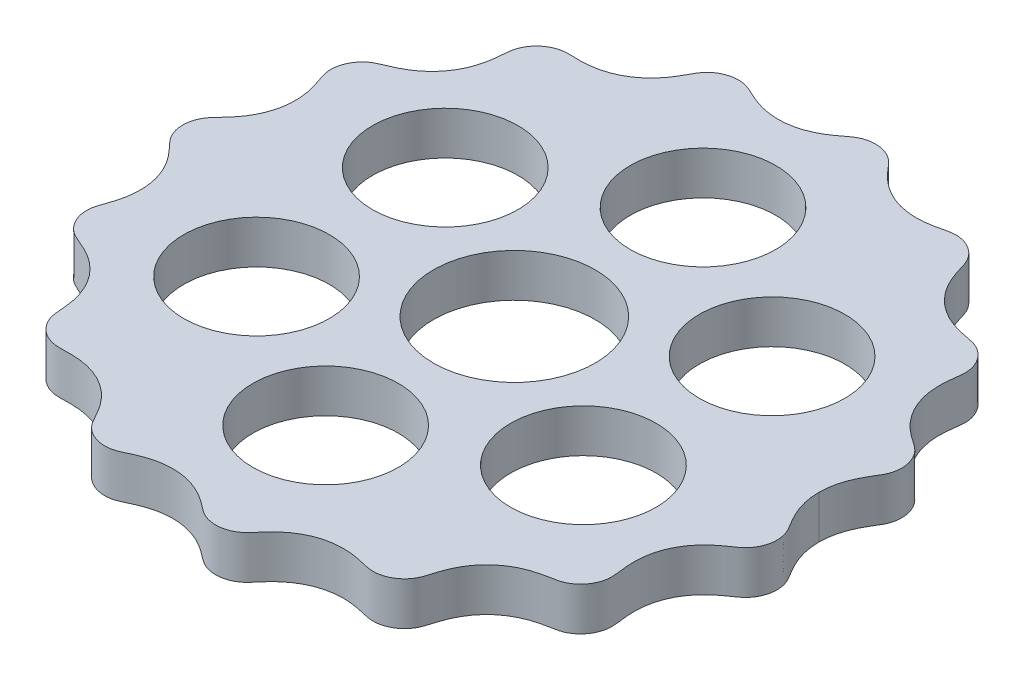
SolidWorks part; units mm, degrees
ref_plane "Front Plane" through (0, 0, 0) normal (0, 0, 1) x (1, 0, 0)
ref_plane "Top Plane" through (0, 0, 0) normal (0, 1, 0) x (1, 0, 0)
ref_plane "Right Plane" through (0, 0, 0) normal (1, 0, 0) x (0, 0, -1)
sketch "Sketch2" plane through (0, 0, 0) normal (0, 1, 0) x (1, 0, 0)
  circle A0 centre (0, 0) radius 35
  circle A1 centre (0, 35) radius 5.5
  circle A2 centre (13.3939, 32.3358) radius 5.5
  circle A3 centre (24.7487, 24.7487) radius 5.5
  circle A4 centre (32.3358, 13.3939) radius 5.5
  circle A5 centre (35, 0) radius 5.5
  circle A6 centre (32.3358, -13.3939) radius 5.5
  circle A7 centre (24.7487, -24.7487) radius 5.5
  circle A8 centre (13.3939, -32.3358) radius 5.5
  circle A9 centre (0, -35) radius 5.5
  circle A10 centre (-13.3939, -32.3358) radius 5.5
  circle A11 centre (-24.7487, -24.7487) radius 5.5
  circle A12 centre (-32.3358, -13.3939) radius 5.5
  circle A13 centre (-35, 0) radius 5.5
  circle A14 centre (-32.3358, 13.3939) radius 5.5
  circle A15 centre (-24.7487, 24.7487) radius 5.5
  circle A16 centre (-13.3939, 32.3358) radius 5.5
  point P14 (0, 0)
  dimension "D1" = 70
  dimension "D2" = 11
  dimension "D3" = 16
sketch "Sketch3" plane through (0, 0, 0) normal (0, 1, 0) x (1, 0, 0)
  line L0 (0, 0) -> (1.25, 0)
  circle A0 centre (1.25, 0) radius 17.5
  circle A1 centre (1.25, 0) radius 7.5
  circle A2 centre (1.25, 17.5) radius 6.75
  circle A3 centre (16.4054, 8.75) radius 6.75
  circle A4 centre (16.4054, -8.75) radius 6.75
  circle A5 centre (1.25, -17.5) radius 6.75
  circle A6 centre (-13.9054, -8.75) radius 6.75
  circle A7 centre (-13.9054, 8.75) radius 6.75
  spline S0 degree 4 poles (31.1366, 6.9847) (31.203, 6.8351) (31.3134, 6.5262) (31.4099, 6.0483) (31.4002, 5.404) (31.2697, 4.8647) (31.0757, 4.4461) (30.8859, 4.1207) (30.7324, 3.8696) (30.5414, 3.5556) (30.3222, 3.1725) (30.1219, 2.7738) (29.947, 2.3583) (29.8196, 1.9985) (29.7291, 1.6992) (29.6529, 1.3958) (29.5916, 1.0892) (29.551, 0.8187) (29.5259, 0.5847) (29.5113, 0.3932) (29.5036, 0.2322) (29.4998, 0.0635) (29.4996, -0.048) (29.5028, -0.2) (29.5088, -0.3457) (29.52, -0.516) (29.5395, -0.7199) (29.5727, -0.9729) (29.6257, -1.2689) (29.6959, -1.5759) (29.7851, -1.8912) (29.9157, -2.2793) (30.102, -2.7349) (30.335, -3.2008) (30.6126, -3.6776) (30.9341, -4.194) (31.2372, -4.7273) (31.4061, -5.3785) (31.4057, -6.1172) (31.2483, -6.8003) (30.9464, -7.4095) (30.5187, -7.9124) (30.0245, -8.2774) (29.5502, -8.595) (29.0554, -8.9568) (28.5566, -9.3788) (28.0713, -9.8763) (27.6188, -10.4563) (27.2335, -11.0884) (26.9232, -11.7651) (26.6937, -12.4782) (26.5492, -13.2173) (26.4929, -13.9285) (26.5065, -14.6008) (26.5673, -15.2309) (26.6512, -15.8162) (26.7167, -16.4473) (26.6264, -17.121) (26.3588, -17.7823) (25.9182, -18.3869) (25.3813, -18.8362) (24.7951, -19.1235) (24.2042, -19.2597) (23.6514, -19.3544) (23.1491, -19.4609) (22.7015, -19.5807) (22.2213, -19.7396) (21.7138, -19.9467) (21.1456, -20.242) (20.5337, -20.6545) (19.9693, -21.14) (19.4622, -21.6938) (19.0208, -22.3087) (18.6716, -22.937) (18.4029, -23.561) (18.1966, -24.1685) (18.0312, -24.7466) (17.8368, -25.3596) (17.4818, -25.9474) (16.963, -26.4532) (16.3026, -26.8344) (15.6052, -27.0309) (14.9186, -27.0444) (14.2906, -26.9063) (13.7073, -26.7605) (13.0779, -26.6354) (12.4032, -26.5561) (11.6845, -26.5443) (10.9313, -26.6191) (10.1981, -26.7814) (9.4956, -27.0274) (8.9144, -27.311) (8.4468, -27.5971) (8.0759, -27.8635) (7.7913, -28.0922) (7.4816, -28.3679) (7.1541, -28.6957) (6.8107, -29.0774) (6.4523, -29.5087) (6.0389, -29.9524) (5.497, -30.3164) (4.8394, -30.5567) (4.0956, -30.636) (3.389, -30.5371) (2.7605, -30.2784) (2.2467, -29.9061) (1.7817, -29.5409) (1.2664, -29.1732) (0.691, -28.8252) (0.0469, -28.5184) (-0.6654, -28.274) (-1.3977, -28.1162) (-2.139, -28.0466) (-2.879, -28.0642) (-3.6075, -28.1661) (-4.2811, -28.3376) (-4.8959, -28.5586) (-5.4566, -28.8062) (-5.9687, -29.0581) (-6.5321, -29.3036) (-7.1813, -29.4226) (-7.8826, -29.3781) (-8.5943, -29.1523) (-9.1983, -28.7803) (-9.6679, -28.2978) (-9.9878, -27.7564) (-10.2605, -27.2379) (-10.5768, -26.6962) (-10.9537, -26.1469) (-11.4088, -25.606) (-11.9502, -25.0925) (-12.5482, -24.6454) (-13.1945, -24.2723) (-13.8806, -23.9779) (-14.596, -23.7658) (-15.292, -23.6421) (-15.9562, -23.5904) (-16.5834, -23.5873) (-17.1688, -23.6104) (-17.7977, -23.6041) (-18.4504, -23.4386) (-19.0745, -23.1016) (-19.6258, -22.5981) (-20.0151, -22.013) (-20.2366, -21.3913) (-20.3057, -20.7807) (-20.3436, -20.2113) (-20.4095, -19.6018) (-20.5256, -18.9589) (-20.7138, -18.2898) (-20.9898, -17.608) (-21.3446, -16.9582) (-21.7755, -16.3511) (-22.2783, -15.7958) (-22.8461, -15.3011) (-23.4339, -14.8967) (-24.0229, -14.5724) (-24.599, -14.31) (-25.1478, -14.0899) (-25.7271, -13.8311) (-26.2654, -13.4161) (-26.7043, -12.8537) (-27.0076, -12.1698) (-27.1282, -11.4802) (-27.084, -10.8288) (-26.9064, -10.2491) (-26.7122, -9.7229) (-26.5247, -9.1481) (-26.3661, -8.5215) (-26.2605, -7.84) (-26.2278, -7.1092) (-26.2792, -6.3728) (-26.4175, -5.6414) (-26.6435, -4.9254) (-26.9163, -4.3218) (-27.1985, -3.8299) (-27.4942, -3.3917) (-27.7933, -3.0033) (-28.1536, -2.592) (-28.5722, -2.1595) (-28.9092, -1.79) (-29.1246, -1.4556) (-29.2527, -1.1931) (-29.3238, -1.0179) (-29.3829, -0.8388) (-29.4302, -0.6555) (-29.4612, -0.4933) (-29.4803, -0.3554) (-29.4914, -0.2338) (-29.4973, -0.1324) (-29.5007, -0.0226) (-29.5, 0.059) (-29.4956, 0.1702) (-29.4865, 0.2945) (-29.4732, 0.4119) (-29.4519, 0.545) (-29.4193, 0.6991) (-29.3684, 0.8884) (-29.2999, 1.0847) (-29.211, 1.2861) (-29.099, 1.4891) (-28.9873, 1.6605) (-28.8641, 1.8237) (-28.732, 1.9798) (-28.56, 2.1688) (-28.311, 2.4302) (-27.9922, 2.7711) (-27.6241, 3.2099) (-27.2613, 3.7219) (-26.8678, 4.4005) (-26.5022, 5.2703) (-26.3208, 6.0377) (-26.2588, 6.6626) (-26.2483, 6.9757) knots 0 0 0 0 0 0.005587 0.011173 0.016507 0.02184 0.02435 0.026861 0.029371 0.031882 0.036903 0.041924 0.044592 0.04726 0.049928 0.052596 0.055264 0.057932 0.059266 0.0606 0.061934 0.063268 0.064442 0.065615 0.066789 0.067963 0.070311 0.072658 0.075454 0.07825 0.081046 0.083842 0.089434 0.095025 0.098832 0.102639 0.110253 0.115841 0.12143 0.127693 0.133956 0.138834 0.143712 0.148591 0.153469 0.159735 0.166 0.172266 0.178532 0.184946 0.191361 0.197775 0.20419 0.209244 0.214299 0.219354 0.224409 0.23082 0.23723 0.243461 0.249691 0.254486 0.25928 0.264075 0.26887 0.271986 0.275101 0.281333 0.287565 0.293796 0.300242 0.306689 0.313135 0.319581 0.324722 0.329863 0.335004 0.340145 0.346588 0.353031 0.359474 0.365917 0.371058 0.376199 0.38134 0.386481 0.392928 0.399374 0.40582 0.412266 0.418498 0.424729 0.427845 0.430961 0.434077 0.437193 0.441987 0.446782 0.451577 0.456371 0.462602 0.468832 0.475243 0.481654 0.486709 0.491763 0.496818 0.501873 0.508287 0.514702 0.521116 0.527531 0.533796 0.540062 0.546328 0.552593 0.557472 0.56235 0.567228 0.572107 0.57837 0.584633 0.590985 0.597337 0.602346 0.607354 0.612363 0.617371 0.623727 0.630083 0.636439 0.642795 0.649151 0.655506 0.661862 0.668218 0.673227 0.678235 0.683244 0.688252 0.694604 0.700957 0.70722 0.713483 0.718361 0.723239 0.728118 0.732996 0.739262 0.745527 0.751793 0.758059 0.764473 0.770888 0.777302 0.783717 0.788771 0.793826 0.798881 0.803936 0.810347 0.816757 0.822988 0.829218 0.834013 0.838807 0.843602 0.848397 0.854628 0.86086 0.867092 0.873323 0.879769 0.886216 0.892662 0.895885 0.899108 0.904249 0.90939 0.914531 0.919672 0.921283 0.922894 0.924505 0.926115 0.927726 0.929337 0.930142 0.930947 0.931753 0.932558 0.933896 0.934564 0.935233 0.93657 0.937908 0.939245 0.940582 0.943257 0.945002 0.946746 0.948491 0.950235 0.95198 0.953724 0.957213 0.962562 0.967911 0.973259 0.978608 0.989304 1 1 1 1 1 construction
  spline S1 degree 4 poles (29.5, 0) (29.5, -0.0299) (29.5005, -0.0898) (29.5028, -0.2) (29.5088, -0.3457) (29.52, -0.516) (29.5395, -0.7199) (29.5727, -0.9729) (29.6257, -1.2689) (29.6959, -1.5759) (29.7851, -1.8912) (29.9157, -2.2793) (30.102, -2.7349) (30.335, -3.2008) (30.6126, -3.6776) (30.9341, -4.194) (31.2372, -4.7273) (31.4061, -5.3785) (31.4057, -6.1172) (31.2483, -6.8003) (30.9464, -7.4095) (30.5187, -7.9124) (30.0245, -8.2774) (29.5502, -8.595) (29.0554, -8.9568) (28.5566, -9.3788) (28.0713, -9.8763) (27.6188, -10.4563) (27.2335, -11.0884) (26.9232, -11.7651) (26.6937, -12.4782) (26.5492, -13.2173) (26.4929, -13.9285) (26.5065, -14.6008) (26.5673, -15.2309) (26.6512, -15.8162) (26.7167, -16.4473) (26.6264, -17.121) (26.3588, -17.7823) (25.9182, -18.3869) (25.3813, -18.8362) (24.7951, -19.1235) (24.2042, -19.2597) (23.6514, -19.3544) (23.1491, -19.4609) (22.7015, -19.5807) (22.2213, -19.7396) (21.7138, -19.9467) (21.1456, -20.242) (20.5337, -20.6545) (19.9693, -21.14) (19.4622, -21.6938) (19.0208, -22.3087) (18.6716, -22.937) (18.4029, -23.561) (18.1966, -24.1685) (18.0312, -24.7466) (17.8368, -25.3596) (17.4818, -25.9474) (16.963, -26.4532) (16.3026, -26.8344) (15.6052, -27.0309) (14.9186, -27.0444) (14.2906, -26.9063) (13.7073, -26.7605) (13.0779, -26.6354) (12.4032, -26.5561) (11.6845, -26.5443) (10.9313, -26.6191) (10.1981, -26.7814) (9.4956, -27.0274) (8.9144, -27.311) (8.4468, -27.5971) (8.0759, -27.8635) (7.7913, -28.0922) (7.4816, -28.3679) (7.1541, -28.6957) (6.8107, -29.0774) (6.4523, -29.5087) (6.0389, -29.9524) (5.497, -30.3164) (4.8394, -30.5567) (4.0956, -30.636) (3.389, -30.5371) (2.7605, -30.2784) (2.2467, -29.9061) (1.7817, -29.5409) (1.2664, -29.1732) (0.691, -28.8252) (0.0469, -28.5184) (-0.6654, -28.274) (-1.3977, -28.1162) (-2.139, -28.0466) (-2.879, -28.0642) (-3.6075, -28.1661) (-4.2811, -28.3376) (-4.8959, -28.5586) (-5.4566, -28.8062) (-5.9687, -29.0581) (-6.5321, -29.3036) (-7.1813, -29.4226) (-7.8826, -29.3781) (-8.5943, -29.1523) (-9.1983, -28.7803) (-9.6679, -28.2978) (-9.9878, -27.7564) (-10.2605, -27.2379) (-10.5768, -26.6962) (-10.9537, -26.1469) (-11.4088, -25.606) (-11.9502, -25.0925) (-12.5482, -24.6454) (-13.1945, -24.2723) (-13.8806, -23.9779) (-14.596, -23.7658) (-15.292, -23.6421) (-15.9562, -23.5904) (-16.5834, -23.5873) (-17.1688, -23.6104) (-17.7977, -23.6041) (-18.4504, -23.4386) (-19.0745, -23.1016) (-19.6258, -22.5981) (-20.0151, -22.013) (-20.2366, -21.3913) (-20.3057, -20.7807) (-20.3436, -20.2113) (-20.4095, -19.6018) (-20.5256, -18.9589) (-20.7138, -18.2898) (-20.9898, -17.608) (-21.3446, -16.9582) (-21.7755, -16.3511) (-22.2783, -15.7958) (-22.8461, -15.3011) (-23.4339, -14.8967) (-24.0229, -14.5724) (-24.599, -14.31) (-25.1478, -14.0899) (-25.7271, -13.8311) (-26.2654, -13.4161) (-26.7043, -12.8537) (-27.0076, -12.1698) (-27.1282, -11.4802) (-27.084, -10.8288) (-26.9064, -10.2491) (-26.7122, -9.7229) (-26.5247, -9.1481) (-26.3661, -8.5215) (-26.2605, -7.84) (-26.2278, -7.1092) (-26.2792, -6.3728) (-26.4175, -5.6414) (-26.6435, -4.9254) (-26.9163, -4.3218) (-27.1985, -3.8299) (-27.4942, -3.3917) (-27.7933, -3.0033) (-28.1536, -2.592) (-28.5722, -2.1595) (-28.9092, -1.79) (-29.1246, -1.4556) (-29.2527, -1.1931) (-29.3238, -1.0179) (-29.3829, -0.8388) (-29.4302, -0.6555) (-29.4612, -0.4933) (-29.4803, -0.3554) (-29.4914, -0.2338) (-29.4973, -0.1324) (-29.4995, -0.0617) (-29.5, -0.0205) (-29.5, 0) knots 0.063268 0.063268 0.063268 0.063268 0.063268 0.064442 0.065615 0.066789 0.067963 0.070311 0.072658 0.075454 0.07825 0.081046 0.083842 0.089434 0.095025 0.098832 0.102639 0.110253 0.115841 0.12143 0.127693 0.133956 0.138834 0.143712 0.148591 0.153469 0.159735 0.166 0.172266 0.178532 0.184946 0.191361 0.197775 0.20419 0.209244 0.214299 0.219354 0.224409 0.23082 0.23723 0.243461 0.249691 0.254486 0.25928 0.264075 0.26887 0.271986 0.275101 0.281333 0.287565 0.293796 0.300242 0.306689 0.313135 0.319581 0.324722 0.329863 0.335004 0.340145 0.346588 0.353031 0.359474 0.365917 0.371058 0.376199 0.38134 0.386481 0.392928 0.399374 0.40582 0.412266 0.418498 0.424729 0.427845 0.430961 0.434077 0.437193 0.441987 0.446782 0.451577 0.456371 0.462602 0.468832 0.475243 0.481654 0.486709 0.491763 0.496818 0.501873 0.508287 0.514702 0.521116 0.527531 0.533796 0.540062 0.546328 0.552593 0.557472 0.56235 0.567228 0.572107 0.57837 0.584633 0.590985 0.597337 0.602346 0.607354 0.612363 0.617371 0.623727 0.630083 0.636439 0.642795 0.649151 0.655506 0.661862 0.668218 0.673227 0.678235 0.683244 0.688252 0.694604 0.700957 0.70722 0.713483 0.718361 0.723239 0.728118 0.732996 0.739262 0.745527 0.751793 0.758059 0.764473 0.770888 0.777302 0.783717 0.788771 0.793826 0.798881 0.803936 0.810347 0.816757 0.822988 0.829218 0.834013 0.838807 0.843602 0.848397 0.854628 0.86086 0.867092 0.873323 0.879769 0.886216 0.892662 0.895885 0.899108 0.904249 0.90939 0.914531 0.919672 0.921283 0.922894 0.924505 0.926115 0.927726 0.929337 0.930142 0.930947 0.931753 0.932558 0.932558 0.932558 0.932558 0.932558
  spline S2 degree 4 poles (29.5, 0) (29.5, 0.0299) (29.5005, 0.0898) (29.5028, 0.2) (29.5088, 0.3457) (29.52, 0.516) (29.5395, 0.7199) (29.5727, 0.9729) (29.6257, 1.2689) (29.6959, 1.5759) (29.7851, 1.8912) (29.9157, 2.2793) (30.102, 2.7349) (30.335, 3.2008) (30.6126, 3.6776) (30.9341, 4.194) (31.2372, 4.7273) (31.4061, 5.3785) (31.4057, 6.1172) (31.2483, 6.8003) (30.9464, 7.4095) (30.5187, 7.9124) (30.0245, 8.2774) (29.5502, 8.595) (29.0554, 8.9568) (28.5566, 9.3788) (28.0713, 9.8763) (27.6188, 10.4563) (27.2335, 11.0884) (26.9232, 11.7651) (26.6937, 12.4782) (26.5492, 13.2173) (26.4929, 13.9285) (26.5065, 14.6008) (26.5673, 15.2309) (26.6512, 15.8162) (26.7167, 16.4473) (26.6264, 17.121) (26.3588, 17.7823) (25.9182, 18.3869) (25.3813, 18.8362) (24.7951, 19.1235) (24.2042, 19.2597) (23.6514, 19.3544) (23.1491, 19.4609) (22.7015, 19.5807) (22.2213, 19.7396) (21.7138, 19.9467) (21.1456, 20.242) (20.5337, 20.6545) (19.9693, 21.14) (19.4622, 21.6938) (19.0208, 22.3087) (18.6716, 22.937) (18.4029, 23.561) (18.1966, 24.1685) (18.0312, 24.7466) (17.8368, 25.3596) (17.4818, 25.9474) (16.963, 26.4532) (16.3026, 26.8344) (15.6052, 27.0309) (14.9186, 27.0444) (14.2906, 26.9063) (13.7073, 26.7605) (13.0779, 26.6354) (12.4032, 26.5561) (11.6845, 26.5443) (10.9313, 26.6191) (10.1981, 26.7814) (9.4956, 27.0274) (8.9144, 27.311) (8.4468, 27.5971) (8.0759, 27.8635) (7.7913, 28.0922) (7.4816, 28.3679) (7.1541, 28.6957) (6.8107, 29.0774) (6.4523, 29.5087) (6.0389, 29.9524) (5.497, 30.3164) (4.8394, 30.5567) (4.0956, 30.636) (3.389, 30.5371) (2.7605, 30.2784) (2.2467, 29.9061) (1.7817, 29.5409) (1.2664, 29.1732) (0.691, 28.8252) (0.0469, 28.5184) (-0.6654, 28.274) (-1.3977, 28.1162) (-2.139, 28.0466) (-2.879, 28.0642) (-3.6075, 28.1661) (-4.2811, 28.3376) (-4.8959, 28.5586) (-5.4566, 28.8062) (-5.9687, 29.0581) (-6.5321, 29.3036) (-7.1813, 29.4226) (-7.8826, 29.3781) (-8.5943, 29.1523) (-9.1983, 28.7803) (-9.6679, 28.2978) (-9.9878, 27.7564) (-10.2605, 27.2379) (-10.5768, 26.6962) (-10.9537, 26.1469) (-11.4088, 25.606) (-11.9502, 25.0925) (-12.5482, 24.6454) (-13.1945, 24.2723) (-13.8806, 23.9779) (-14.596, 23.7658) (-15.292, 23.6421) (-15.9562, 23.5904) (-16.5834, 23.5873) (-17.1688, 23.6104) (-17.7977, 23.6041) (-18.4504, 23.4386) (-19.0745, 23.1016) (-19.6258, 22.5981) (-20.0151, 22.013) (-20.2366, 21.3913) (-20.3057, 20.7807) (-20.3436, 20.2113) (-20.4095, 19.6018) (-20.5256, 18.9589) (-20.7138, 18.2898) (-20.9898, 17.608) (-21.3446, 16.9582) (-21.7755, 16.3511) (-22.2783, 15.7958) (-22.8461, 15.3011) (-23.4339, 14.8967) (-24.0229, 14.5724) (-24.599, 14.31) (-25.1478, 14.0899) (-25.7271, 13.8311) (-26.2654, 13.4161) (-26.7043, 12.8537) (-27.0076, 12.1698) (-27.1282, 11.4802) (-27.084, 10.8288) (-26.9064, 10.2491) (-26.7122, 9.7229) (-26.5247, 9.1481) (-26.3661, 8.5215) (-26.2605, 7.84) (-26.2278, 7.1092) (-26.2792, 6.3728) (-26.4175, 5.6414) (-26.6435, 4.9254) (-26.9163, 4.3218) (-27.1985, 3.8299) (-27.4942, 3.3917) (-27.7933, 3.0033) (-28.1536, 2.592) (-28.5722, 2.1595) (-28.9092, 1.79) (-29.1246, 1.4556) (-29.2527, 1.1931) (-29.3238, 1.0179) (-29.3829, 0.8388) (-29.4302, 0.6555) (-29.4612, 0.4933) (-29.4803, 0.3554) (-29.4914, 0.2338) (-29.4973, 0.1324) (-29.4995, 0.0617) (-29.5, 0.0205) (-29.5, 0) knots 0.063268 0.063268 0.063268 0.063268 0.063268 0.064442 0.065615 0.066789 0.067963 0.070311 0.072658 0.075454 0.07825 0.081046 0.083842 0.089434 0.095025 0.098832 0.102639 0.110253 0.115841 0.12143 0.127693 0.133956 0.138834 0.143712 0.148591 0.153469 0.159735 0.166 0.172266 0.178532 0.184946 0.191361 0.197775 0.20419 0.209244 0.214299 0.219354 0.224409 0.23082 0.23723 0.243461 0.249691 0.254486 0.25928 0.264075 0.26887 0.271986 0.275101 0.281333 0.287565 0.293796 0.300242 0.306689 0.313135 0.319581 0.324722 0.329863 0.335004 0.340145 0.346588 0.353031 0.359474 0.365917 0.371058 0.376199 0.38134 0.386481 0.392928 0.399374 0.40582 0.412266 0.418498 0.424729 0.427845 0.430961 0.434077 0.437193 0.441987 0.446782 0.451577 0.456371 0.462602 0.468832 0.475243 0.481654 0.486709 0.491763 0.496818 0.501873 0.508287 0.514702 0.521116 0.527531 0.533796 0.540062 0.546328 0.552593 0.557472 0.56235 0.567228 0.572107 0.57837 0.584633 0.590985 0.597337 0.602346 0.607354 0.612363 0.617371 0.623727 0.630083 0.636439 0.642795 0.649151 0.655506 0.661862 0.668218 0.673227 0.678235 0.683244 0.688252 0.694604 0.700957 0.70722 0.713483 0.718361 0.723239 0.728118 0.732996 0.739262 0.745527 0.751793 0.758059 0.764473 0.770888 0.777302 0.783717 0.788771 0.793826 0.798881 0.803936 0.810347 0.816757 0.822988 0.829218 0.834013 0.838807 0.843602 0.848397 0.854628 0.86086 0.867092 0.873323 0.879769 0.886216 0.892662 0.895885 0.899108 0.904249 0.90939 0.914531 0.919672 0.921283 0.922894 0.924505 0.926115 0.927726 0.929337 0.930142 0.930947 0.931753 0.932558 0.932558 0.932558 0.932558 0.932558
  point P20 (1.25, 0)
  dimension "D2" = 35
  dimension "D3" = 13.5
  dimension "D4" = 15
  dimension "D1" = 1.25
  dimension "D5" = 6
extrude "Boss-Extrude1" add sketch "Sketch3" along normal blind 4 contours S1 S2 A7 A0 A2 A3 A4 A5 A6 | A7 A0 A6 A5 A4 A3 A2 A1
sketch "Sketch4" plane through (0, 0, 0) normal (0, -1, 0) x (-1, 0, 0)
  circle A0 centre (0, 0) radius 17.5
  circle A1 centre (0, 17.5) radius 5.5
  circle A2 centre (15.1554, 8.75) radius 5.5
  circle A3 centre (15.1554, -8.75) radius 5.5
  circle A4 centre (0, -17.5) radius 5.5
  circle A5 centre (-15.1554, -8.75) radius 5.5
  circle A6 centre (-15.1554, 8.75) radius 5.5
  point P16 (0, 0)
  dimension "D2" = 11
  dimension "D1" = 35
  dimension "D3" = 6
equation "\"R_SUN\"=35"
equation "\"D1@Sketch2\"=2*\"R_SUN\""
equation "\"R_ROLL\"=5.5"
equation "\"D2@Sketch2\"=2*\"R_ROLL\""
equation "\"GRATIO\"=15"
equation "\"D3@Sketch2\"=\"GRATIO\"+1"
equation "\"RHO\"=1.25"
equation "\"D1@Sketch3\"=\"RHO\""
equation "\"D_PIN_SPACE\"=35"
equation "\"D_PIN\"=11"
equation "\"D3@Sketch3\"=\"D_PIN\"+2*\"RHO\""
equation "\"D_IN\"=15"
equation "\"D4@Sketch3\"=\"D_IN\""
equation "\"NUM_PINS\"=6"
equation "\"D5@Sketch3\"=\"NUM_PINS\""
equation "\"THICK\"=4"
equation "\"D1@Boss-Extrude1\"=\"THICK\""
equation "\"D_BOLTS\"=35"
equation "\"D1@Sketch4\"=\"D_BOLTS\""
equation "\"R_BEAR\"=11"
equation "\"D2@Sketch4\"=\"R_BEAR\""
equation "\"NUM_BOLT\"=6"
equation "\"D3@Sketch4\"=\"NUM_BOLT\""
